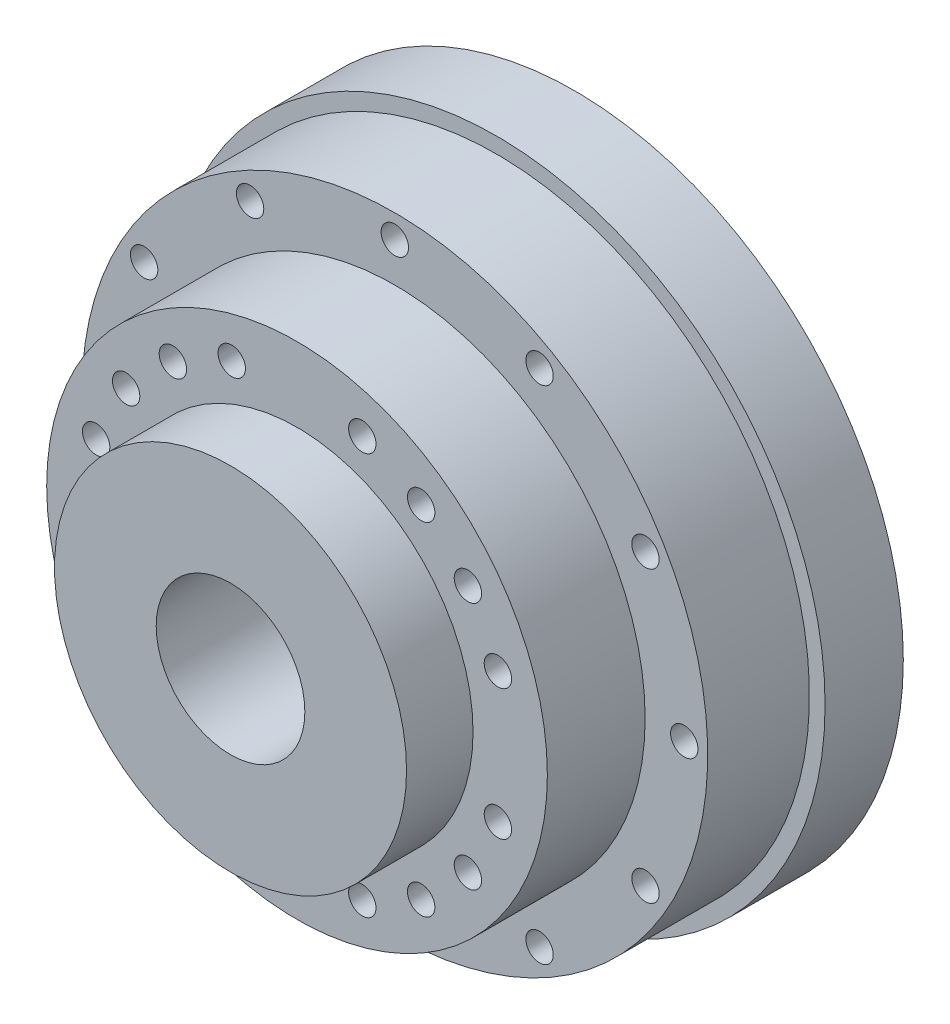
SolidWorks part; units mm, degrees
ref_plane "Спереди" through (0, 0, 0) normal (0, 0, 1) x (1, 0, 0)
ref_plane "Сверху" through (0, 0, 0) normal (0, 1, 0) x (1, 0, 0)
ref_plane "Справа" through (0, 0, 0) normal (1, 0, 0) x (0, 0, -1)
other "Configuration Table"
sketch "Эскиз1" plane through (0, 0, 0) normal (0, 0, 1) x (1, 0, 0)
  circle A0 centre (0, 0) radius 42
  dimension "D1" = 84
extrude "Бобышка-Вытянуть1" add sketch "Эскиз1" along normal blind 10
sketch "Эскиз2" plane through (0, 0, 10) normal (0, 0, 1) x (1, 0, 0)
  circle A0 centre (0, 0) radius 40
  dimension "D1" = 80
extrude "Бобышка-Вытянуть2" add sketch "Эскиз2" along normal blind 13
sketch "Эскиз3" plane through (0, 0, 23) normal (0, 0, 1) x (1, 0, 0)
  circle A0 centre (0, 0) radius 32
  dimension "D1" = 64
extrude "Бобышка-Вытянуть3" add sketch "Эскиз3" along normal blind 12.5
sketch "Эскиз4" plane through (0, 0, 35.5) normal (0, 0, 1) x (1, 0, 0)
  circle A0 centre (0, 0) radius 22.5
  dimension "D1" = 45
extrude "Бобышка-Вытянуть4" add sketch "Эскиз4" along normal blind 8.5
sketch "Эскиз5" plane through (0, 0, 0) normal (0, 0, -1) x (-1, 0, 0)
  circle A0 centre (0, 0) radius 22.5
  dimension "D1" = 45
extrude "Бобышка-Вытянуть5" add sketch "Эскиз5" along normal blind 5.5
sketch "Эскиз6" plane through (0, 0, -5.5) normal (0, 0, -1) x (-1, 0, 0)
  circle A0 centre (0, 0) radius 12.5
  dimension "D1" = 25
extrude "Бобышка-Вытянуть6" add sketch "Эскиз6" along normal blind 7
sketch "Эскиз7" plane through (0, 0, -12.5) normal (0, 0, -1) x (-1, 0, 0)
  circle A0 centre (0, 0) radius 9.5
  dimension "D1" = 19
extrude "Вырез-Вытянуть1" cut sketch "Эскиз7" against normal up to surface (56.5 mm away) up to face at (22.5, 0, 44)
sketch "Эскиз8" plane through (0, 0, 23) normal (0, 0, 1) x (1, 0, 0)
  circle A0 centre (0, 37) radius 1.75
  circle A1 centre (18.5, 32.0429) radius 1.75
  circle A2 centre (32.0429, 18.5) radius 1.75
  circle A3 centre (37, 0) radius 1.75
  circle A4 centre (32.0429, -18.5) radius 1.75
  circle A5 centre (18.5, -32.0429) radius 1.75
  circle A6 centre (0, -37) radius 1.75
  circle A7 centre (-18.5, -32.0429) radius 1.75
  circle A8 centre (-32.0429, -18.5) radius 1.75
  circle A9 centre (-37, 0) radius 1.75
  circle A10 centre (-32.0429, 18.5) radius 1.75
  circle A11 centre (-18.5, 32.0429) radius 1.75
  point P19 (0, 0)
  dimension "D2" = 3.5
  dimension "D1" = 37
  dimension "D3" = 12
extrude "Вырез-Вытянуть2" cut sketch "Эскиз8" against normal up to surface (23 mm away) up to face at (-22.5, 0, 0)
sketch "Эскиз9" plane through (0, 0, 35.5) normal (0, 0, 1) x (1, 0, 0)
  line L0 (-8.3435, 25.6785) -> (0, 0) construction
  line L1 (0, 0) -> (0, 19.5382) construction
  circle A0 centre (-8.3435, 25.6785) radius 1.75
  circle A2 centre (8.3435, 25.6785) radius 1.75
  circle A3 centre (15.8702, 21.8435) radius 1.75
  circle A4 centre (21.8435, 15.8702) radius 1.75
  circle A5 centre (25.6785, 8.3435) radius 1.75
  circle A7 centre (25.6785, -8.3435) radius 1.75
  circle A8 centre (21.8435, -15.8702) radius 1.75
  circle A9 centre (15.8702, -21.8435) radius 1.75
  circle A10 centre (8.3435, -25.6785) radius 1.75
  circle A12 centre (-8.3435, -25.6785) radius 1.75
  circle A13 centre (-15.8702, -21.8435) radius 1.75
  circle A14 centre (-21.8435, -15.8702) radius 1.75
  circle A15 centre (-25.6785, -8.3435) radius 1.75
  circle A17 centre (-25.6785, 8.3435) radius 1.75
  circle A18 centre (-21.8435, 15.8702) radius 1.75
  circle A19 centre (-15.8702, 21.8435) radius 1.75
  circle A20 centre (0, 27) radius 1.75 [skipped]
  circle A21 centre (27, 0) radius 1.75 [skipped]
  circle A22 centre (0, -27) radius 1.75 [skipped]
  circle A23 centre (-27, 0) radius 1.75 [skipped]
  point P27 (0, 0)
  dimension "D1" = 3.5
  dimension "D2" = 27
  dimension "D4" = 18
  dimension "D3" = 20
extrude "Вырез-Вытянуть3" cut sketch "Эскиз9" against normal blind 12
ref_plane "Плоскость1" through (0, 12.5, 0) normal (0, 1, 0) x (1, 0, 0)
sketch "Эскиз11" plane through (0, 12.5, 0) normal (0, 1, 0) x (1, 0, 0)
  line L0 (12.5, 12.5) -> (-12.5, 12.5) construction
  circle A0 centre (0, 10) radius 1.5
  dimension "D1" = 3
  dimension "D2" = 2.5
extrude "Вырез-Вытянуть4" cut sketch "Эскиз11" against normal up to surface (3 mm away)
pattern_circular "Круговой массив1" count 3 over 360 about axis through (0, 0, 70.8701) along (0, 0, -1) of "Вырез-Вытянуть4"
